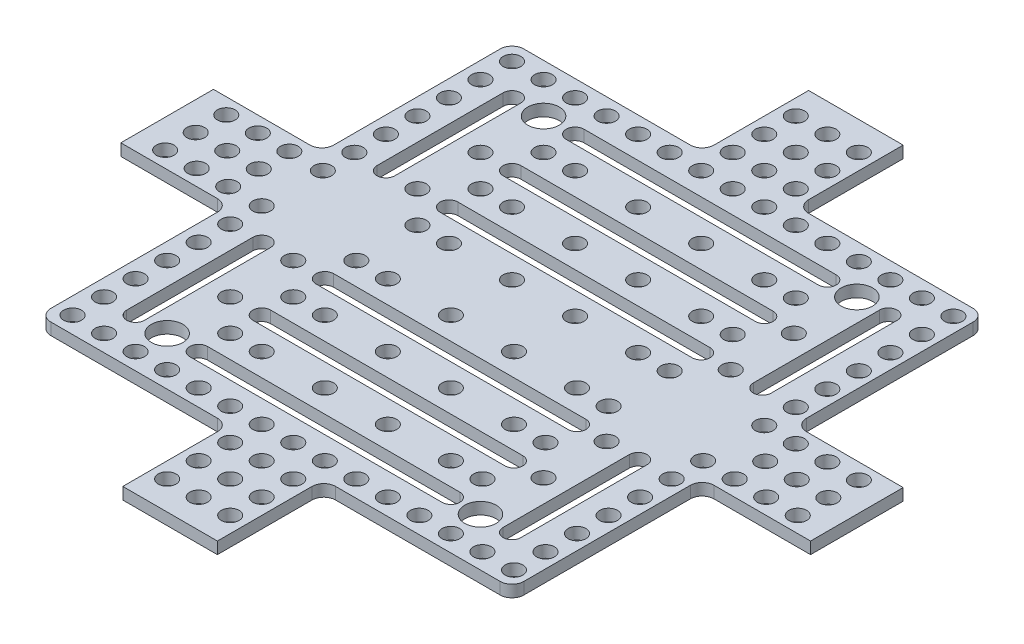
SolidWorks part; units mm, degrees
ref_plane "前视基准面" through (0, 0, 0) normal (0, 0, 1) x (1, 0, 0)
ref_plane "上视基准面" through (0, 0, 0) normal (0, 1, 0) x (1, 0, 0)
ref_plane "右视基准面" through (0, 0, 0) normal (1, 0, 0) x (0, 0, -1)
sketch "草图1" plane through (0, 0, 0) normal (0, 1, 0) x (1, 0, 0)
  line L1 (-60, -60) -> (-11.75, -60)
  line L2 (-60, -60) -> (-60, -11.75)
  line L3 (-60, 60) -> (-11.75, 60)
  line L4 (60, -60) -> (60, -11.75)
  line L5 (-60, -60) -> (60, 60) construction
  line L6 (-60, 60) -> (60, -60) construction
  line L34 (-7.75, -55.75) -> (-7.75, -63.75) construction
  line L35 (-11.75, -60) -> (-7.75, -60) construction
  line L36 (-11.75, -60) -> (-11.75, -87)
  line L37 (-11.75, -87) -> (12.25, -87)
  line L38 (-55.75, -55.75) -> (-47.75, -55.75) construction
  line L39 (-55.75, -55.75) -> (-55.75, -47.75) construction
  line L40 (-47.75, -15.75) -> (-47.75, -47.75) construction
  line L41 (-45.5, -15.75) -> (-45.5, -47.75)
  line L42 (-50, -15.75) -> (-50, -47.75)
  line L43 (0, -55) -> (0, 55) construction
  line L44 (47.75, -15.75) -> (47.75, -47.75) construction
  line L45 (45.5, -15.75) -> (45.5, -47.75)
  line L46 (50, -15.75) -> (50, -47.75)
  line L47 (-31.75, -55.75) -> (-31.75, -39.75) construction
  line L48 (-31.75, -31.75) -> (32.25, -31.75) construction
  line L51 (-31.75, -29.5) -> (32.25, -29.5)
  line L54 (-31.75, -47.75) -> (32.25, -47.75) construction
  line L55 (-31.75, -45.5) -> (32.25, -45.5)
  line L56 (-31.75, -50) -> (32.25, -50)
  line L57 (56.25, -55.75) -> (56.25, -47.75) construction
  line L58 (-31.75, -34) -> (32.25, -34)
  line L59 (-31.75, -15.75) -> (32.25, -15.75) construction
  line L60 (-31.75, -13.5) -> (32.25, -13.5)
  line L61 (-31.75, -18) -> (32.25, -18)
  line L62 (39.75, -31.75) -> (39.75, -15.75) construction
  line L63 (-55, 0) -> (55, 0) construction
  line L64 (-31.75, 15.75) -> (32.25, 15.75) construction
  line L65 (-31.75, 13.5) -> (32.25, 13.5)
  line L66 (-31.75, 18) -> (32.25, 18)
  line L67 (-31.75, 47.75) -> (32.25, 47.75) construction
  line L68 (-31.75, 45.5) -> (32.25, 45.5)
  line L69 (-31.75, 50) -> (32.25, 50)
  line L70 (-31.75, 31.75) -> (32.25, 31.75) construction
  line L71 (-31.75, 29.5) -> (32.25, 29.5)
  line L72 (-31.75, 34) -> (32.25, 34)
  line L73 (47.75, 15.75) -> (47.75, 47.75) construction
  line L74 (45.5, 15.75) -> (45.5, 47.75)
  line L75 (50, 15.75) -> (50, 47.75)
  line L76 (-47.75, 15.75) -> (-47.75, 47.75) construction
  line L77 (-45.5, 15.75) -> (-45.5, 47.75)
  line L78 (-50, 15.75) -> (-50, 47.75)
  line L79 (12.25, -60) -> (12.25, -87)
  line L92 (8.25, -55.75) -> (16.25, -55.75) construction
  line L93 (-15.75, -55.75) -> (-7.75, -55.75) construction
  line L106 (-7.75, -60) -> (12.25, -60) construction
  line L107 (12.25, -60) -> (60, -60)
  line L108 (-7.75, -60) -> (12.25, -60) construction
  line L109 (-11.75, -60) -> (-7.75, -60) construction
  line L110 (12.25, 60) -> (12.25, 87)
  line L111 (-11.75, 87) -> (12.25, 87)
  line L112 (-11.75, 60) -> (-11.75, 87)
  line L113 (12.25, 60) -> (60, 60)
  line L114 (56.25, 15.75) -> (56.25, 7.75) construction
  line L115 (56.25, -7.75) -> (56.25, -15.75) construction
  line L116 (56.25, 7.75) -> (56.25, -7.75) construction
  line L117 (60, 11.75) -> (87.5, 11.75)
  line L118 (60, 11.75) -> (60, -11.75) construction
  line L119 (60, -11.75) -> (87.5, -11.75)
  line L120 (87.5, 11.75) -> (87.5, -11.75)
  line L121 (64.25, 7.75) -> (72.25, 7.75) construction
  line L122 (60, -11.75) -> (60, 11.75) construction
  line L123 (60, 11.75) -> (60, 60)
  line L124 (-60, -11.75) -> (-87.5, -11.75)
  line L125 (-87.5, 11.75) -> (-87.5, -11.75)
  line L126 (-60, 11.75) -> (-87.5, 11.75)
  line L127 (-60, -11.75) -> (-60, 11.75) construction
  line L128 (-60, 11.75) -> (-60, 60)
  line L130 (0, 10) -> (0, -10) construction
  circle A6 centre (-55.75, -55.75) radius 2.25
  circle A7 centre (-47.75, -55.75) radius 2.25
  circle A8 centre (-39.75, -55.75) radius 2.25
  circle A9 centre (-31.75, -55.75) radius 2.25
  circle A45 centre (-23.75, -55.75) radius 2.25
  circle A46 centre (-15.75, -55.75) radius 2.25
  circle A47 centre (-7.75, -55.75) radius 2.25
  circle A48 centre (0.25, -55.75) radius 2.25
  circle A49 centre (8.25, -55.75) radius 2.25
  circle A50 centre (16.25, -55.75) radius 2.25
  circle A51 centre (24.25, -55.75) radius 2.25
  circle A52 centre (32.25, -55.75) radius 2.25
  circle A53 centre (40.25, -55.75) radius 2.25
  circle A54 centre (48.25, -55.75) radius 2.25
  circle A55 centre (56.25, -55.75) radius 2.25
  circle A56 centre (-55.75, -47.75) radius 2.25
  circle A57 centre (-55.75, -39.75) radius 2.25
  circle A58 centre (-55.75, -31.75) radius 2.25
  circle A59 centre (-55.75, -23.75) radius 2.25
  circle A60 centre (-55.75, -15.75) radius 2.25
  circle A61 centre (-55.75, -7.75) radius 2.25
  arc A62 (-45.5, -15.75) -> (-50, -15.75) centre (-47.75, -15.75) ccw
  arc A63 (-50, -47.75) -> (-45.5, -47.75) centre (-47.75, -47.75) ccw
  circle A64 centre (-39.75, -47.75) radius 4
  circle A65 centre (39.75, -47.75) radius 4
  arc A66 (45.5, -15.75) -> (50, -15.75) centre (47.75, -15.75) cw
  arc A67 (50, -47.75) -> (45.5, -47.75) centre (47.75, -47.75) cw
  arc A74 (-31.75, -45.5) -> (-31.75, -50) centre (-31.75, -47.75) ccw
  arc A75 (32.25, -50) -> (32.25, -45.5) centre (32.25, -47.75) ccw
  circle A76 centre (56.25, -47.75) radius 2.25
  circle A77 centre (56.25, -39.75) radius 2.25
  circle A78 centre (56.25, -31.75) radius 2.25
  circle A79 centre (56.25, -23.75) radius 2.25
  circle A80 centre (56.25, -15.75) radius 2.25
  circle A81 centre (56.25, -7.75) radius 2.25
  circle A84 centre (-31.75, -39.75) radius 2.25
  circle A85 centre (-23.75, -39.75) radius 2.25
  circle A86 centre (-7.75, -39.75) radius 2.25
  circle A87 centre (8.25, -39.75) radius 2.25
  circle A88 centre (24.25, -39.75) radius 2.25
  circle A89 centre (32.25, -39.75) radius 2.25
  arc A90 (-31.75, -29.5) -> (-31.75, -34) centre (-31.75, -31.75) ccw
  arc A91 (32.25, -34) -> (32.25, -29.5) centre (32.25, -31.75) ccw
  circle A93 centre (-39.75, -31.75) radius 2.25
  circle A94 centre (39.75, -31.75) radius 2.25
  circle A96 centre (-31.75, -23.75) radius 2.25
  circle A97 centre (-23.75, -23.75) radius 2.25
  circle A98 centre (-7.75, -23.75) radius 2.25
  circle A99 centre (8.25, -23.75) radius 2.25
  circle A100 centre (24.25, -23.75) radius 2.25
  circle A101 centre (32.25, -23.75) radius 2.25
  circle A102 centre (39.75, -15.75) radius 2.25
  circle A103 centre (-39.75, -15.75) radius 2.25
  circle A104 centre (-31.75, -7.75) radius 2.25
  circle A105 centre (-23.75, -7.75) radius 2.25
  circle A106 centre (-7.75, -7.75) radius 2.25
  circle A107 centre (8.25, -7.75) radius 2.25
  circle A108 centre (24.25, -7.75) radius 2.25
  circle A109 centre (32.25, -7.75) radius 2.25
  arc A110 (-31.75, -13.5) -> (-31.75, -18) centre (-31.75, -15.75) ccw
  arc A111 (32.25, -18) -> (32.25, -13.5) centre (32.25, -15.75) ccw
  arc A112 (-31.75, 13.5) -> (-31.75, 18) centre (-31.75, 15.75) cw
  arc A113 (32.25, 18) -> (32.25, 13.5) centre (32.25, 15.75) cw
  circle A114 centre (32.25, 39.75) radius 2.25
  circle A115 centre (-31.75, 39.75) radius 2.25
  circle A116 centre (-23.75, 39.75) radius 2.25
  circle A117 centre (-7.75, 39.75) radius 2.25
  circle A118 centre (8.25, 39.75) radius 2.25
  circle A119 centre (24.25, 39.75) radius 2.25
  circle A120 centre (32.25, 23.75) radius 2.25
  circle A121 centre (24.25, 23.75) radius 2.25
  circle A122 centre (8.25, 23.75) radius 2.25
  circle A123 centre (-7.75, 23.75) radius 2.25
  circle A124 centre (-23.75, 23.75) radius 2.25
  circle A125 centre (-31.75, 23.75) radius 2.25
  circle A126 centre (-39.75, 31.75) radius 2.25
  circle A127 centre (-39.75, 47.75) radius 4
  circle A128 centre (-47.75, 55.75) radius 2.25
  circle A129 centre (-39.75, 55.75) radius 2.25
  circle A130 centre (-31.75, 55.75) radius 2.25
  circle A131 centre (-23.75, 55.75) radius 2.25
  circle A132 centre (-15.75, 55.75) radius 2.25
  circle A133 centre (-7.75, 55.75) radius 2.25
  circle A134 centre (0.25, 55.75) radius 2.25
  circle A135 centre (32.25, 55.75) radius 2.25
  circle A136 centre (24.25, 55.75) radius 2.25
  circle A137 centre (8.25, 55.75) radius 2.25
  circle A138 centre (16.25, 55.75) radius 2.25
  arc A139 (-31.75, 45.5) -> (-31.75, 50) centre (-31.75, 47.75) cw
  arc A140 (32.25, 50) -> (32.25, 45.5) centre (32.25, 47.75) cw
  arc A141 (-31.75, 29.5) -> (-31.75, 34) centre (-31.75, 31.75) cw
  arc A142 (32.25, 34) -> (32.25, 29.5) centre (32.25, 31.75) cw
  circle A143 centre (39.75, 31.75) radius 2.25
  circle A144 centre (39.75, 47.75) radius 4
  circle A145 centre (40.25, 55.75) radius 2.25
  circle A146 centre (48.25, 55.75) radius 2.25
  circle A147 centre (56.25, 55.75) radius 2.25
  circle A148 centre (56.25, 47.75) radius 2.25
  circle A149 centre (56.25, 39.75) radius 2.25
  arc A150 (45.5, 15.75) -> (50, 15.75) centre (47.75, 15.75) ccw
  arc A151 (50, 47.75) -> (45.5, 47.75) centre (47.75, 47.75) ccw
  circle A152 centre (56.25, 31.75) radius 2.25
  circle A153 centre (56.25, 23.75) radius 2.25
  circle A154 centre (56.25, 15.75) radius 2.25
  circle A155 centre (56.25, 7.75) radius 2.25
  circle A156 centre (39.75, 15.75) radius 2.25
  circle A157 centre (32.25, 7.75) radius 2.25
  circle A158 centre (24.25, 7.75) radius 2.25
  circle A159 centre (8.25, 7.75) radius 2.25
  circle A160 centre (-7.75, 7.75) radius 2.25
  circle A161 centre (-23.75, 7.75) radius 2.25
  circle A162 centre (-31.75, 7.75) radius 2.25
  circle A163 centre (-39.75, 15.75) radius 2.25
  arc A164 (-45.5, 15.75) -> (-50, 15.75) centre (-47.75, 15.75) cw
  arc A165 (-50, 47.75) -> (-45.5, 47.75) centre (-47.75, 47.75) cw
  circle A166 centre (-55.75, 55.75) radius 2.25
  circle A167 centre (-55.75, 47.75) radius 2.25
  circle A168 centre (-55.75, 39.75) radius 2.25
  circle A169 centre (-55.75, 31.75) radius 2.25
  circle A170 centre (-55.75, 23.75) radius 2.25
  circle A171 centre (-55.75, 15.75) radius 2.25
  circle A172 centre (-55.75, 7.75) radius 2.25
  circle A173 centre (-7.75, -63.75) radius 2.25
  circle A174 centre (0.25, -63.75) radius 2.25
  circle A175 centre (8.25, -63.75) radius 2.25
  circle A176 centre (-7.75, -71.75) radius 2.25
  circle A177 centre (0.25, -71.75) radius 2.25
  circle A178 centre (8.25, -71.75) radius 2.25
  circle A179 centre (-7.75, -79.75) radius 2.25
  circle A180 centre (0.25, -79.75) radius 2.25
  circle A181 centre (8.25, -79.75) radius 2.25
  circle A182 centre (8.25, 79.75) radius 2.25
  circle A183 centre (8.25, 71.75) radius 2.25
  circle A184 centre (0.25, 71.75) radius 2.25
  circle A185 centre (0.25, 79.75) radius 2.25
  circle A186 centre (-7.75, 79.75) radius 2.25
  circle A187 centre (-7.75, 71.75) radius 2.25
  circle A188 centre (-7.75, 63.75) radius 2.25
  circle A189 centre (0.25, 63.75) radius 2.25
  circle A190 centre (8.25, 63.75) radius 2.25
  circle A191 centre (64.25, 7.75) radius 2.25
  circle A192 centre (72.25, 7.75) radius 2.25
  circle A193 centre (80.25, 7.75) radius 2.25
  circle A194 centre (72.25, 0) radius 2.25
  circle A195 centre (80.25, 0) radius 2.25
  circle A196 centre (72.25, -7.75) radius 2.25
  circle A197 centre (80.25, -7.75) radius 2.25
  circle A198 centre (64.25, 0) radius 2.25
  circle A199 centre (64.25, -7.75) radius 2.25
  circle A200 centre (-80.25, -7.75) radius 2.25
  circle A201 centre (-72.25, -7.75) radius 2.25
  circle A202 centre (-64.25, -7.75) radius 2.25
  circle A203 centre (-64.25, 0) radius 2.25
  circle A204 centre (-72.25, 0) radius 2.25
  circle A205 centre (-80.25, 0) radius 2.25
  circle A206 centre (-80.25, 7.75) radius 2.25
  circle A207 centre (-72.25, 7.75) radius 2.25
  circle A208 centre (-64.25, 7.75) radius 2.25
  point P0 (0, 0)
  point P9 (12.25, -55.75)
  point P32 (-11.75, -55.75)
  point P70 (56.25, 0)
  point P90 (0, 0)
  point P91 (56.25, 11.75)
  point P92 (56.25, -11.75)
  point P145 (-47.75, -31.75)
  point P150 (0.25, -47.75)
  point P161 (47.75, -31.75)
  point P182 (0.25, -31.75)
  point P225 (0.25, -15.75)
  point P250 (0.25, 15.75)
  point P307 (0.25, 47.75)
  point P314 (0.25, 31.75)
  point P335 (47.75, 31.75)
  point P366 (-47.75, 31.75)
  point P392 (1.2541, 9.9211)
  point P393 (0, 0)
  point P394 (0, 0)
  point P395 (0, 0)
  point P396 (0, 0)
  point P397 (0.25, 9.1027)
  point P398 (0, 6.4772)
  dimension "D8" = 8
  dimension "D9" = 3
  dimension "D12" = 8
  dimension "D10" = 3
  dimension "D14" = 4.5
  dimension "D15" = 4.25
  dimension "D16" = 20
  dimension "D17" = 1
  dimension "D22" = 2.25
  dimension "D23" = 8
  dimension "D24" = 2.25
  dimension "D27" = 3
  dimension "D29" = 2.25
  dimension "D30" = 2
  dimension "D31" = 4.5
  dimension "D5" = 4.5
  dimension "D13" = 4.25
  dimension "D1" = 120
  dimension "D2" = 120
  dimension "D4" = 7.25
  dimension "D6" = 8
  dimension "D7" = 4
  dimension "D18" = 8
  dimension "D19" = 7
  dimension "D21" = 8
  dimension "D26" = 8
  dimension "D28" = 16
  dimension "D32" = 16
  dimension "D11" = 7.25
  dimension "D20" = 15
  dimension "D25" = 7
extrude "凸台-拉伸1" add sketch "草图1" along normal blind 3
fillet "圆角1" radius 3 12 edges at (-60, 1.5, -11.75) (-60, 1.5, -60) (-11.75, 1.5, -60) (12.25, 1.5, -60) (60, 1.5, -60) (60, 1.5, -11.75) (60, 1.5, 11.75) (60, 1.5, 60) (12.25, 1.5, 60) (-11.75, 1.5, 60) (-60, 1.5, 60) (-60, 1.5, 11.75)
